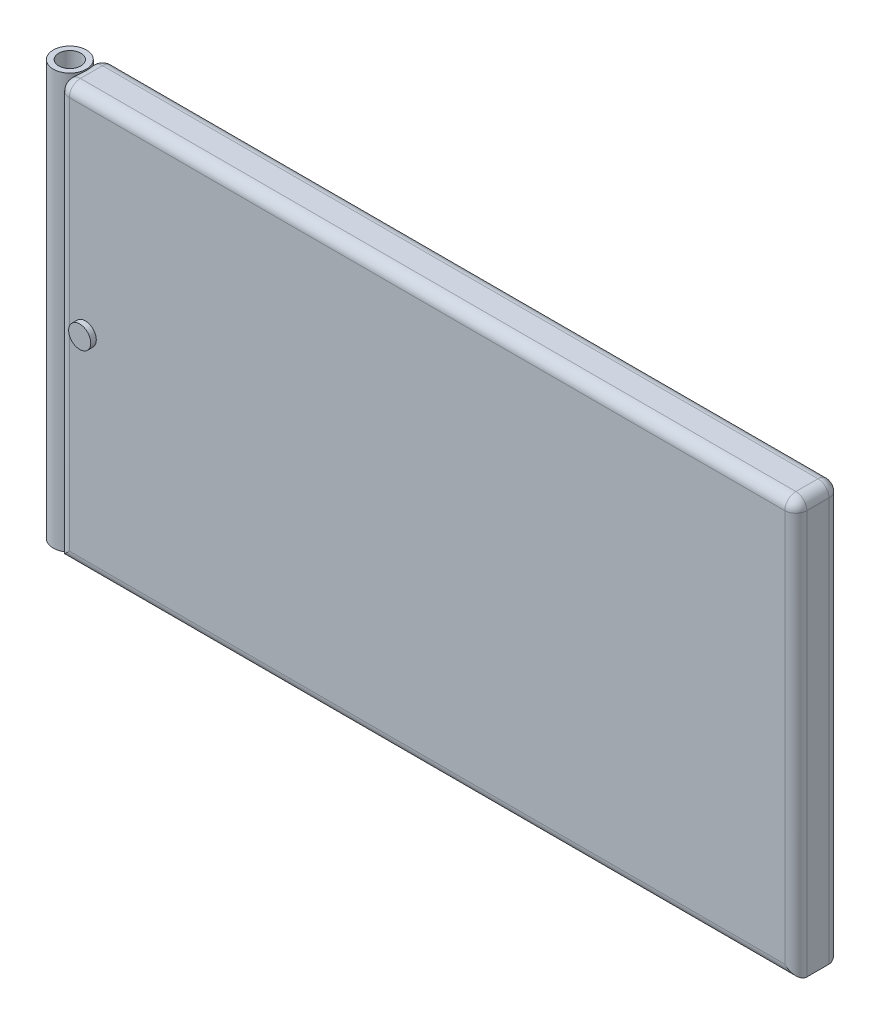
SolidWorks part; units mm, degrees
material "Custom Plastic"
ref_plane "Front Plane" through (0, 0, 0) normal (0, 0, 1) x (1, 0, 0)
ref_plane "Top Plane" through (0, 0, 0) normal (0, 1, 0) x (1, 0, 0)
ref_plane "Right Plane" through (0, 0, 0) normal (1, 0, 0) x (0, 0, -1)
sketch "Sketch1" plane through (0, 0, 0) normal (0, 0, 1) x (1, 0, 0)
  line L1 (-857.1857, 239.2977) -> (476.2143, 239.2977)
  line L2 (-857.1857, 239.2977) -> (-857.1857, -510.7023)
  line L3 (-857.1857, -510.7023) -> (476.2143, -510.7023)
  line L4 (476.2143, 239.2977) -> (476.2143, -510.7023)
  dimension "D1" = 1333.4
  dimension "D2" = 750
extrude "Boss-Extrude1" add sketch "Sketch1" along normal blind 80
fillet "Fillet1" radius 20 1 edges at (-190.4857, 239.2977, 0)
fillet "Fillet2" radius 20 11 edges at (476.2143, 239.2977, 50) (476.2143, 233.4398, 5.8579) (-857.1857, 239.2977, 50) (-857.1857, 233.4398, 5.8579) (476.2143, -145.7023, 0) (476.2143, -135.7023, 80) (-857.1857, -135.7023, 80) (-857.1857, -145.7023, 0) (-190.4857, -510.7023, 80) (-190.4857, -510.7023, 0) (-190.4857, 239.2977, 80)
sketch "Sketch2" plane through (0, 239.2977, 0) normal (0, 1, 0) x (1, 0, 0)
  circle A0 centre (-876.2403, -40) radius 20
  circle A1 centre (-876.2403, -40) radius 30
  dimension "D1" = 10
extrude "Boss-Extrude2" add sketch "Sketch2" against normal blind 750
sketch "Sketch3" plane through (0, 239.2977, 0) normal (0, 1, 0) x (1, 0, 0)
  circle A0 centre (-876.2403, -40) radius 20
extrude "Cut-Extrude1" cut sketch "Sketch3" against normal blind 750
sketch "Sketch4" plane through (0, 0, 80) normal (0, 0, 1) x (1, 0, 0)
  circle A0 centre (-808.3932, -135.7023) radius 20
extrude "Boss-Extrude3" add sketch "Sketch4" along normal blind 10
